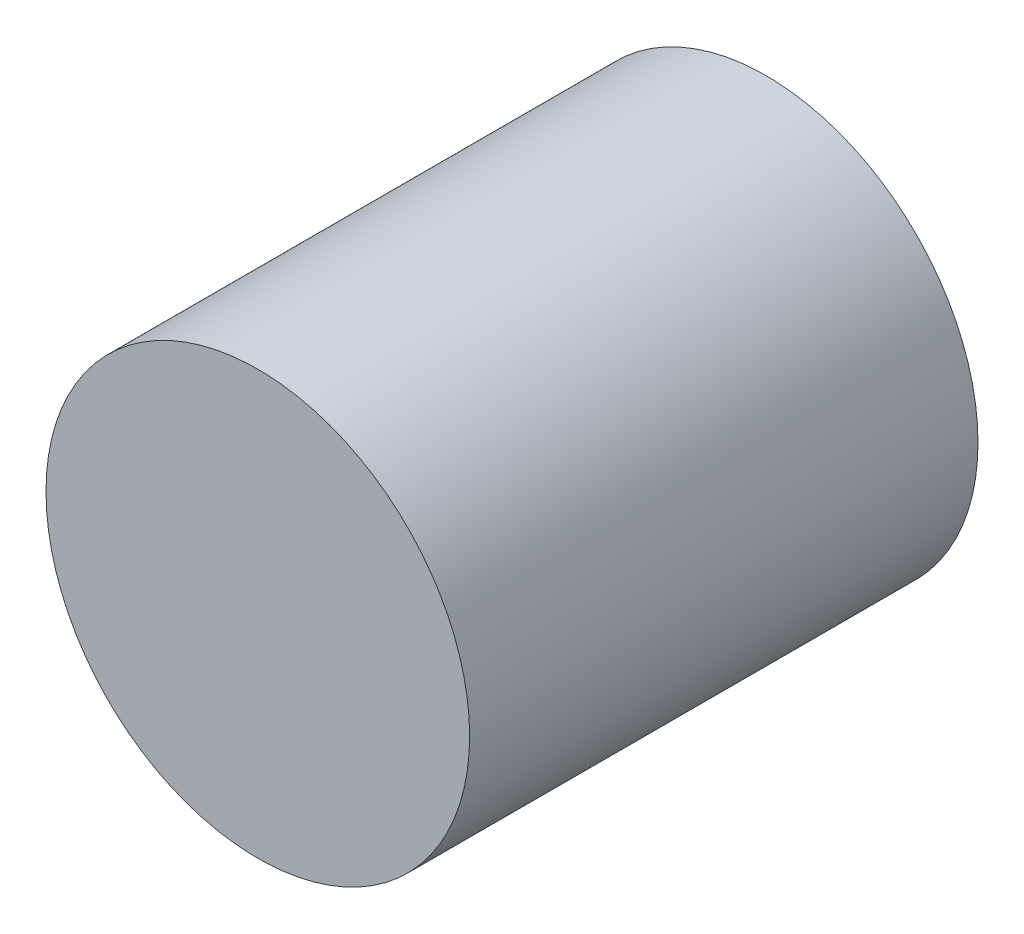
SolidWorks part; units mm, degrees
ref_plane "Front Plane" through (0, 0, 0) normal (0, 0, 1) x (1, 0, 0)
ref_plane "Top Plane" through (0, 0, 0) normal (0, 1, 0) x (1, 0, 0)
ref_plane "Right Plane" through (0, 0, 0) normal (1, 0, 0) x (0, 0, -1)
sketch "Sketch1" plane through (0, 0, 0) normal (0, 0, 1) x (1, 0, 0)
  circle A0 centre (0, 0) radius 25
  dimension "D1" = 50
extrude "Boss-Extrude1" add sketch "Sketch1" along normal blind 60
